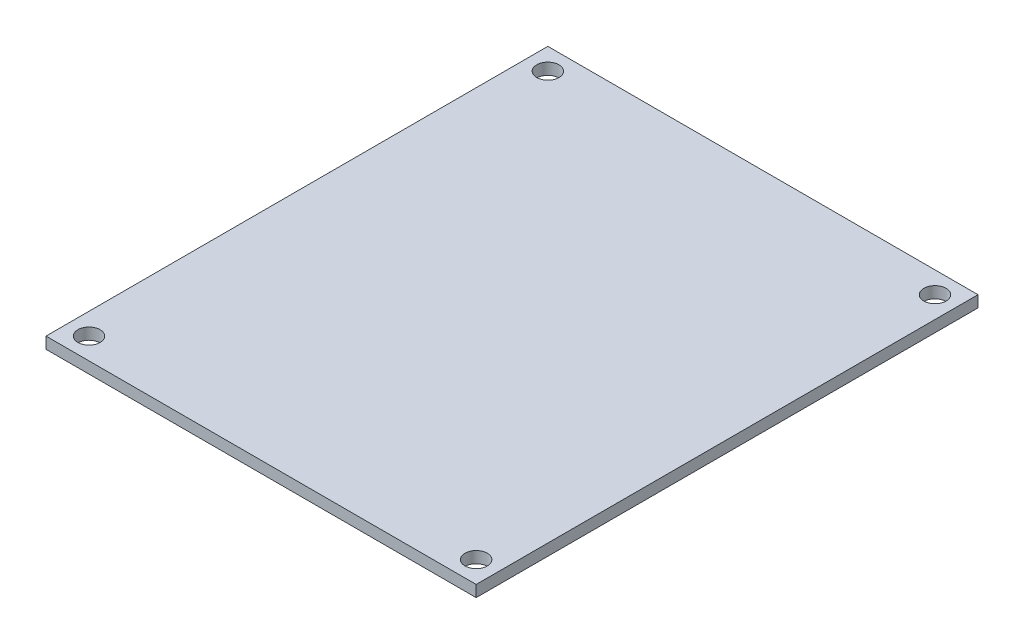
SolidWorks part; units mm, degrees
ref_plane "前视基准面" through (0, 0, 0) normal (0, 0, 1) x (1, 0, 0)
ref_plane "上视基准面" through (0, 0, 0) normal (0, 1, 0) x (1, 0, 0)
ref_plane "右视基准面" through (0, 0, 0) normal (1, 0, 0) x (0, 0, -1)
sketch "草图1" plane through (0, 0, 0) normal (0, 1, 0) x (1, 0, 0)
  line L1 (-30, 35) -> (30, 35)
  line L2 (-30, 35) -> (-30, -35)
  line L3 (-30, -35) -> (30, -35)
  line L4 (30, 35) -> (30, -35)
  line L5 (-30, 35) -> (30, -35) construction
  line L6 (-30, -35) -> (30, 35) construction
  line L7 (-27, 32) -> (27, 32) construction
  line L8 (-27, 32) -> (-27, -32) construction
  line L9 (-27, -32) -> (27, -32) construction
  line L10 (27, 32) -> (27, -32) construction
  line L11 (-27, 32) -> (27, -32) construction
  line L12 (-27, -32) -> (27, 32) construction
  circle A0 centre (27, 32) radius 1.55
  circle A1 centre (-27, 32) radius 1.55
  circle A2 centre (27, -32) radius 1.55
  circle A3 centre (-27, -32) radius 1.55
  point P0 (0, 0)
  point P6 (0, 0)
  dimension "D5" = 3.1
  dimension "D6" = 3.1
  dimension "D7" = 3.1
  dimension "D8" = 3.1
  dimension "D1" = 70
  dimension "D2" = 60
  dimension "D3" = 64
  dimension "D4" = 54
extrude "凸台-拉伸1" add sketch "草图1" along normal blind 1.6
